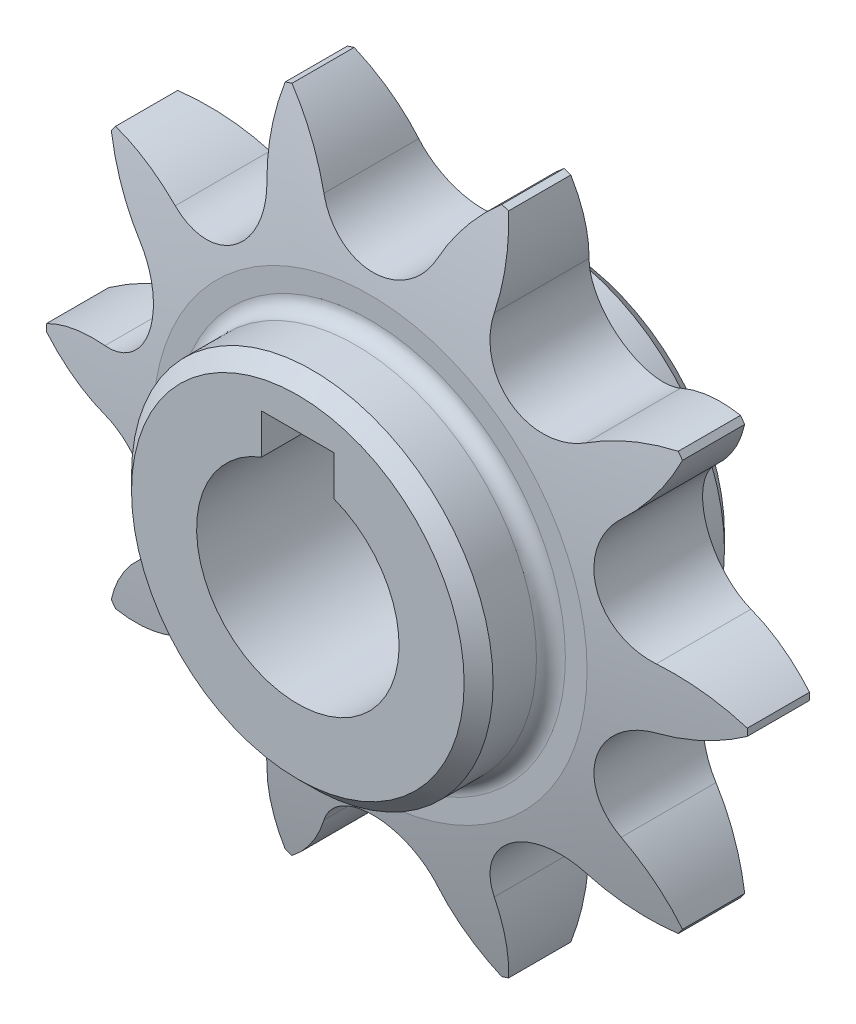
SolidWorks part; units mm, degrees
material "1.7033 (34Cr4)"
ref_plane "Спереди" through (0, 0, 0) normal (0, 0, 1) x (1, 0, 0)
ref_plane "Сверху" through (0, 0, 0) normal (0, 1, 0) x (1, 0, 0)
ref_plane "Справа" through (0, 0, 0) normal (1, 0, 0) x (0, 0, -1)
sketch "Эскиз1" plane through (0, 0, 0) normal (0, 0, 1) x (1, 0, 0)
  line L3 (19.748, 14.0422) -> (19.4574, 14.4422)
  line L4 (24.2303, -0.2472) -> (24.2303, 0.2472)
  line L5 (19.4574, -14.4422) -> (19.748, -14.0422)
  line L6 (7.2525, -23.1207) -> (7.7226, -22.968)
  line L7 (-7.7226, -22.968) -> (-7.2525, -23.1207)
  line L8 (-19.748, -14.0422) -> (-19.4574, -14.4422)
  line L9 (-24.2303, 0.2472) -> (-24.2303, -0.2472)
  line L10 (-19.4574, 14.4422) -> (-19.748, 14.0422)
  line L11 (-7.2525, 23.1207) -> (-7.7226, 22.968)
  line L12 (7.7226, 22.968) -> (7.2525, 23.1207)
  arc A1 (7.8602, 17.4827) -> (14.1981, 12.878) centre (12.0784, 16.6245) ccw
  arc A2 (19.4574, 14.4422) -> (14.1981, 12.878) centre (20.2325, 2.2123) ccw
  arc A3 (16.6351, 9.5237) -> (19.748, 14.0422) centre (8.3562, 18.5586) ccw
  arc A4 (16.6351, 9.5237) -> (19.056, 2.0731) centre (19.5433, 6.35) ccw
  arc A5 (24.2303, 0.2472) -> (19.056, 2.0731) centre (17.6688, -10.1026) ccw
  arc A6 (19.056, -2.0731) -> (24.2303, -0.2472) centre (17.6688, 10.1026) ccw
  arc A7 (19.056, -2.0731) -> (16.6351, -9.5237) centre (19.5433, -6.35) ccw
  arc A8 (19.748, -14.0422) -> (16.6351, -9.5237) centre (8.3562, -18.5586) ccw
  arc A9 (14.1981, -12.878) -> (19.4574, -14.4422) centre (20.2325, -2.2123) ccw
  arc A10 (14.1981, -12.878) -> (7.8602, -17.4827) centre (12.0784, -16.6245) ccw
  arc A11 (7.7226, -22.968) -> (7.8602, -17.4827) centre (-4.1482, -19.9258) ccw
  arc A12 (3.917, -18.7639) -> (7.2525, -23.1207) centre (15.068, -13.6821) ccw
  arc A13 (3.917, -18.7639) -> (-3.917, -18.7639) centre (0, -20.549) ccw
  arc A14 (-7.2525, -23.1207) -> (-3.917, -18.7639) centre (-15.068, -13.6821) ccw
  arc A15 (-7.8602, -17.4827) -> (-7.7226, -22.968) centre (4.1482, -19.9258) ccw
  arc A16 (-7.8602, -17.4827) -> (-14.1981, -12.878) centre (-12.0784, -16.6245) ccw
  arc A17 (-19.4574, -14.4422) -> (-14.1981, -12.878) centre (-20.2325, -2.2123) ccw
  arc A18 (-16.6351, -9.5237) -> (-19.748, -14.0422) centre (-8.3562, -18.5586) ccw
  arc A19 (-16.6351, -9.5237) -> (-19.056, -2.0731) centre (-19.5433, -6.35) ccw
  arc A20 (-24.2303, -0.2472) -> (-19.056, -2.0731) centre (-17.6688, 10.1026) ccw
  arc A21 (-19.056, 2.0731) -> (-24.2303, 0.2472) centre (-17.6688, -10.1026) ccw
  arc A22 (-19.056, 2.0731) -> (-16.6351, 9.5237) centre (-19.5433, 6.35) ccw
  arc A23 (-19.748, 14.0422) -> (-16.6351, 9.5237) centre (-8.3562, 18.5586) ccw
  arc A24 (-14.1981, 12.878) -> (-19.4574, 14.4422) centre (-20.2325, 2.2123) ccw
  arc A25 (-14.1981, 12.878) -> (-7.8602, 17.4827) centre (-12.0784, 16.6245) ccw
  arc A26 (-7.7226, 22.968) -> (-7.8602, 17.4827) centre (4.1482, 19.9258) ccw
  arc A27 (-3.917, 18.7639) -> (-7.2525, 23.1207) centre (-15.068, 13.6821) ccw
  arc A28 (-3.917, 18.7639) -> (3.917, 18.7639) centre (0, 20.549) ccw
  arc A29 (7.2525, 23.1207) -> (3.917, 18.7639) centre (15.068, 13.6821) ccw
  arc A30 (7.8602, 17.4827) -> (7.7226, 22.968) centre (-4.1482, 19.9258) ccw
extrude "Бобышка-Вытянуть1" add sketch "Эскиз1" along normal mid plane 8
sketch "Эскиз3" plane through (0, 0, 4) normal (0, 0, 1) x (1, 0, 0)
  circle A0 centre (0, 0) radius 7
  dimension "D1" = 14
extrude "Вырез-Вытянуть1" cut sketch "Эскиз3" against normal blind 10
sketch "Эскиз4" plane through (0, 0, -4) normal (0, 0, 1) x (1, 0, 0)
  circle A0 centre (0, 0) radius 7 construction
  circle A1 centre (0, 0) radius 7
  circle A2 centre (0, 0) radius 12.5
  dimension "D1" = 25
extrude "Бобышка-Вытянуть2" add sketch "Эскиз4" against normal blind 5
sketch "Эскиз8" plane through (0, 0, 4) normal (0, 0, 1) x (1, 0, 0)
  circle A0 centre (0, 0) radius 7 construction
  circle A1 centre (0, 0) radius 7
  circle A2 centre (0, 0) radius 12.5
  dimension "D1" = 25
extrude "Бобышка-Вытянуть3" add sketch "Эскиз8" along normal blind 5
sketch "Эскиз7" plane through (0, 0, 0) normal (0, 0, 1) x (1, 0, 0)
  line L0 (0, 14.3797) -> (0, 5.8144) construction
  line L1 (-2.5, 9.3) -> (2.5, 9.3)
  line L2 (-2.5, 9.3) -> (-2.5, 6.5383)
  line L3 (-2.5, 6.5383) -> (2.5, 6.5383)
  line L4 (2.5, 6.5383) -> (2.5, 9.3)
  line L5 (-24.6275, 7) -> (-21.4402, 7) construction
  circle A0 centre (0, 0) radius 7 construction
  dimension "D1" = 2.3
  dimension "D2" = 5
extrude "Вырез-Вытянуть2" cut sketch "Эскиз7" against normal through all both and the other way through all
sketch "Эскиз9" plane through (0, 0, 0) normal (0, 1, 0) x (1, 0, 0)
  line L0 (0, 5.9237) -> (0, 50005.9237) construction
  line L1 (-15, -4) -> (-27, -4)
  line L2 (-27, -4) -> (-27, -1.4174)
  line L3 (7.7226, -4) -> (8.1062, -4) construction
  arc A0 (-27, -1.4174) -> (-15, -4) centre (0, 94.8686) ccw
  dimension "D1" = 200
  dimension "D2" = 15
  dimension "D3" = 12
revolve "Вырез-Повернуть1" cut sketch "Эскиз9" angle 360 about L0
mirror "Зеркальное отражение2" about plane through (0, 0, 0) normal (0, 0, 1) of "Вырез-Повернуть1"
fillet "Скругление1" radius 1 2 edges at (12.5, 0, -4) (12.5, 0, 4)
chamfer "Фаска2" distance 1 angle 45 2 edges at (12.5, 0, -9) (12.5, 0, 9)
